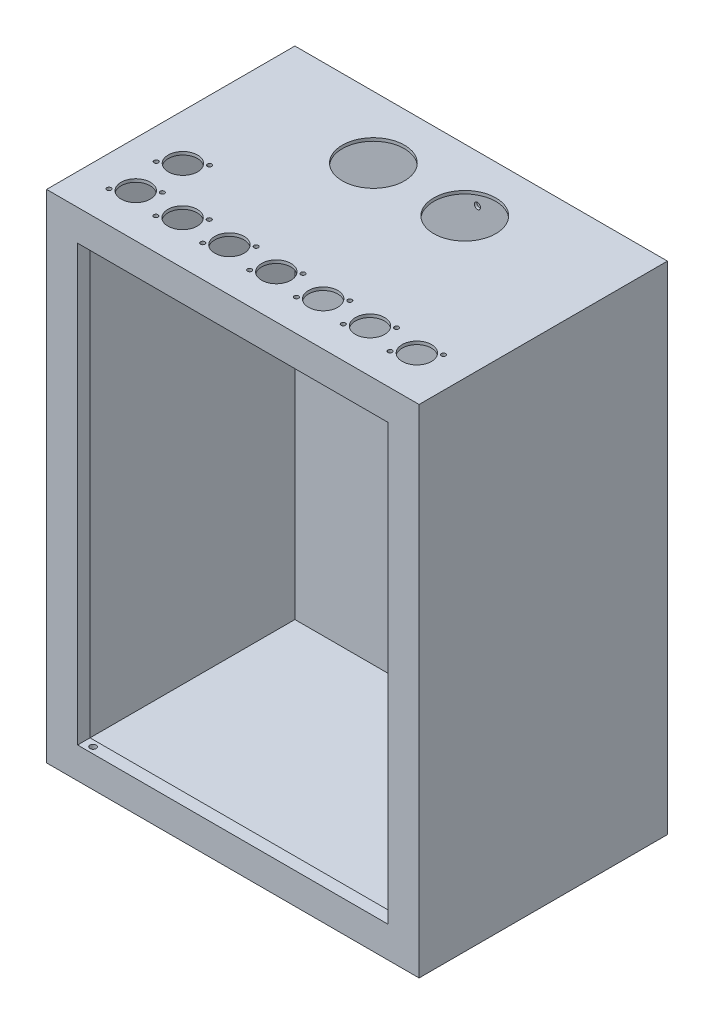
SolidWorks part; units mm, degrees
ref_plane "Front Plane" through (0, 0, 0) normal (0, 0, 1) x (1, 0, 0)
ref_plane "Top Plane" through (0, 0, 0) normal (0, 1, 0) x (1, 0, 0)
ref_plane "Right Plane" through (0, 0, 0) normal (1, 0, 0) x (0, 0, -1)
sketch "Sketch1" plane through (0, 0, 0) normal (0, 1, 0) x (1, 0, 0)
  line L1 (150, -100) -> (-150, -100)
  line L2 (150, -100) -> (150, 100)
  line L3 (150, 100) -> (-150, 100)
  line L4 (-150, -100) -> (-150, 100)
  line L5 (150, -100) -> (-150, 100) construction
  line L6 (150, 100) -> (-150, -100) construction
  point P0 (0, 0)
  dimension "D1" = 200
  dimension "D2" = 300
extrude "Boss-Extrude1" add sketch "Sketch1" along normal blind 400
sketch "Sketch2" plane through (0, 0, 100) normal (0, 0, 1) x (1, 0, 0)
  line L0 (-147, 397) -> (-147, 3)
  line L1 (-147, 3) -> (147, 3)
  line L2 (147, 3) -> (147, 397)
  line L3 (147, 397) -> (-147, 397)
  line L4 (-150, 0) -> (150, 0)
  line L5 (150, 0) -> (150, 400)
  line L6 (150, 400) -> (-150, 400)
  line L7 (-150, 400) -> (-150, 0)
  line L8 (-150, 0) -> (150, 0)
  line L9 (150, 0) -> (150, 400)
  line L10 (150, 400) -> (-150, 400)
  line L11 (-150, 400) -> (-150, 0)
  dimension "D1" = 0
  dimension "D2" = 3
extrude "Cut-Extrude1" cut sketch "Sketch2" against normal blind 197 contours L0 L1 L2 L3
ref_plane "Plane1" through (0, 0, 100) normal (0, 0, 1) x (1, 0, 0)
sketch "Sketch3" plane through (0, 0, 100) normal (0, 0, 1) x (1, 0, 0)
  line L0 (-147, 3) -> (147, 3) construction
  line L1 (147, 3) -> (147, 397) construction
  line L2 (147, 397) -> (-147, 397) construction
  line L3 (-147, 397) -> (-147, 3) construction
  line L4 (-147, 3) -> (147, 3)
  line L5 (147, 3) -> (147, 397)
  line L6 (147, 397) -> (-147, 397)
  line L7 (-147, 397) -> (-147, 3)
  line L8 (-125, 375) -> (-125, 25)
  line L9 (-125, 25) -> (125, 25)
  line L10 (125, 25) -> (125, 375)
  line L11 (125, 375) -> (-125, 375)
  line L12 (-150, 400) -> (-150, 0) construction
  dimension "D2" = 25
  dimension "D1" = 22
extrude "Boss-Extrude2" add sketch "Sketch3" against normal blind 10
sketch "Sketch4" plane through (0, 0, -97) normal (0, 0, 1) x (1, 0, 0)
  line L0 (-125, 375) -> (-125, 25) construction
  line L5 (-125, 200) -> (125, 200) construction
  line L6 (125, 375) -> (-125, 375) construction
  circle A0 centre (0, 365) radius 2.5
  circle A1 centre (0, 35) radius 2.5
  dimension "D1" = 125
  dimension "D2" = 10
  dimension "D3" = 5
extrude "Cut-Extrude2" cut sketch "Sketch4" against normal blind 2
sketch "Sketch5" plane through (0, 397, 0) normal (0, -1, 0) x (1, 0, 0)
  line L1 (-147, 90) -> (147, 90)
  line L2 (-147, 90) -> (-147, -97)
  line L3 (-147, -97) -> (147, -97)
  line L4 (147, 90) -> (147, -97)
extrude "Cut-Extrude3" cut sketch "Sketch5" against normal blind 0.5
sketch "Sketch6" plane through (0, 400, 0) normal (0, 1, 0) x (1, 0, 0)
  line L0 (-150, 100) -> (-150, -100) construction
  line L1 (-113.2, -65) -> (-75.4667, -65) construction
  line L2 (-125, -65) -> (-125, -100) construction
  line L3 (-150, -100) -> (150, -100) construction
  line L4 (-125, -65) -> (113.2, -65) construction
  line L5 (125, -65) -> (125, -100) construction
  line L6 (113.2, -65) -> (125, -65) construction
  line L7 (150, -100) -> (150, 100) construction
  line L8 (-113.2, -65) -> (-113.2, -27) construction
  circle A0 centre (-113.2, -65) radius 11.8
  circle A1 centre (-75.4667, -65) radius 11.8
  circle A2 centre (-37.7333, -65) radius 11.8
  circle A3 centre (0, -65) radius 11.8
  circle A4 centre (37.7333, -65) radius 11.8
  circle A5 centre (75.4667, -65) radius 11.8
  circle A6 centre (113.2, -65) radius 11.8
  circle A7 centre (-113.2, -27) radius 11.8
  dimension "D3" = 23.6
  dimension "D8" = 23.6
  dimension "D1" = 25
  dimension "D2" = 35
  dimension "D4" = 36.8
  dimension "D6" = 37.7333
  dimension "D7" = 38
  dimension "D5" = 7
extrude "Cut-Extrude4" cut sketch "Sketch6" against normal up to next
sketch "Sketch7" plane through (0, 400, 0) normal (0, 1, 0) x (1, 0, 0)
  line L0 (0, 0) -> (0, 50) construction
  line L2 (-11.8, 50) -> (0, 50) construction
  line L3 (0, 50) -> (11.8, 50) construction
  line L5 (-11.8, 50) -> (-61.8, 50) construction
  circle A1 centre (-75.4667, -65) radius 11.8 construction
  circle A2 centre (-36.8, 50) radius 25
  circle A3 centre (36.8, 50) radius 25
  dimension "D5" = 11.8
  dimension "D7" = 36.8
  dimension "D1" = 50
  dimension "D2" = 50
  dimension "D4" = 11.8
extrude "Cut-Extrude5" cut sketch "Sketch7" against normal up to next
sketch "Sketch8" plane through (0, 400, 0) normal (0, 1, 0) x (1, 0, 0)
  line L0 (-150, -76.25) -> (-125.2, -76.25) construction
  line L1 (-150, 100) -> (-150, -100) construction
  line L2 (-150, -100) -> (150, -100) construction
  line L3 (-150, -72.75) -> (-125.2, -72.75) construction
  line L4 (-125.2, -72.75) -> (-125.2, -76.25) construction
  line L5 (-125.2, -74.5) -> (101.2, -74.5) construction
  circle A0 centre (-125.2, -74.5) radius 1.75
  circle A1 centre (-87.47, -74.5) radius 1.75
  circle A2 centre (-49.74, -74.5) radius 1.75
  circle A3 centre (-12.01, -74.5) radius 1.75
  circle A4 centre (25.72, -74.5) radius 1.75
  circle A5 centre (63.45, -74.5) radius 1.75
  circle A6 centre (101.18, -74.5) radius 1.75
  circle A7 centre (75.4667, -65) radius 11.8 construction
  dimension "D1" = 24.8
  dimension "D2" = 23.75
  dimension "D3" = 3.5
  dimension "D4" = 226.4
  dimension "D6" = 25.7133
  dimension "D5" = 7
extrude "Cut-Extrude7" cut sketch "Sketch8" against normal up to next
sketch "Sketch9" plane through (0, 400, 0) normal (0, 1, 0) x (1, 0, 0)
  line L0 (-150, -53.75) -> (-101.2, -53.75) construction
  line L1 (-150, 100) -> (-150, -100) construction
  line L2 (-101.2, -53.75) -> (-101.2, -100) construction
  line L3 (-150, -100) -> (150, -100) construction
  circle A0 centre (-101.2, -55.5) radius 1.75
  circle A1 centre (-63.47, -55.5) radius 1.75
  circle A2 centre (-25.74, -55.5) radius 1.75
  circle A3 centre (11.99, -55.5) radius 1.75
  circle A4 centre (49.72, -55.5) radius 1.75
  circle A5 centre (87.45, -55.5) radius 1.75
  circle A6 centre (125.18, -55.5) radius 1.75
  circle A7 centre (-75.4667, -65) radius 11.8 construction
  dimension "D4" = 3.5
  dimension "D1" = 48.8
  dimension "D2" = 46.25
  dimension "D3" = 7
  dimension "D5" = 11.9967
extrude "Cut-Extrude8" cut sketch "Sketch9" against normal up to next
sketch "Sketch11" plane through (0, 400, 0) normal (0, 1, 0) x (1, 0, 0)
  circle A0 centre (-125.2, -74.5) radius 1.75 construction
  circle A4 centre (-125.2, -36.5) radius 1.75
  circle A5 centre (-101.2, -17.5) radius 1.75
  dimension "D1" = 3.5
  dimension "D2" = 24
  dimension "D3" = 38
  dimension "D4" = 57
extrude "Cut-Extrude9" cut sketch "Sketch11" against normal up to next
sketch "Sketch12" plane through (0, 375, 0) normal (0, -1, 0) x (1, 0, 0)
  line L0 (-125, 95) -> (-120, 95) construction
  line L1 (-125, 90) -> (-125, 100) construction
  circle A0 centre (-117.5, 95) radius 2.5
  dimension "D2" = 5
  dimension "D1" = 5
extrude "Cut-Extrude10" cut sketch "Sketch12" against normal blind 5 and the other way blind 355
